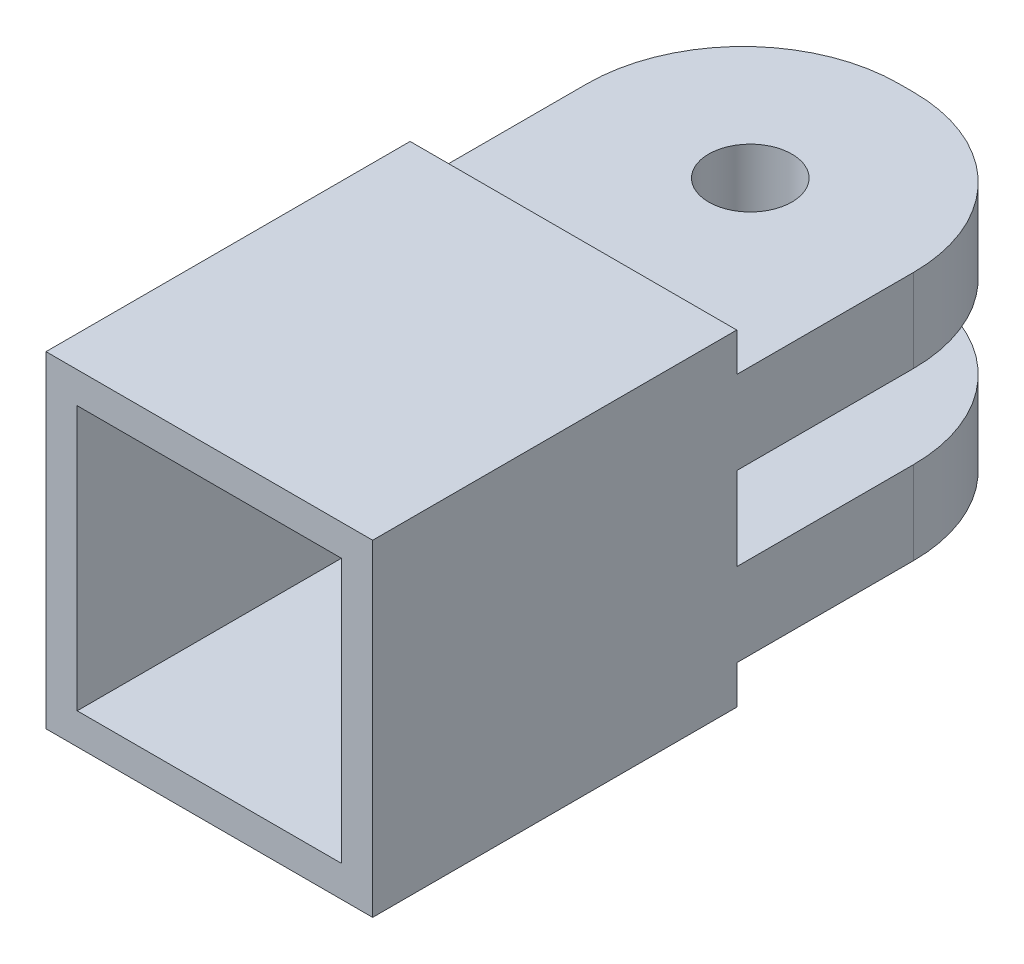
SolidWorks part; units mm, degrees
ref_plane "Front Plane" through (0, 0, 0) normal (0, 0, 1) x (1, 0, 0)
ref_plane "Top Plane" through (0, 0, 0) normal (0, 1, 0) x (1, 0, 0)
ref_plane "Right Plane" through (0, 0, 0) normal (1, 0, 0) x (0, 0, -1)
sketch "Sketch1" plane through (0, 0, 0) normal (0, 0, 1) x (1, 0, 0)
  line L0 (0, 34.2563) -> (0, -38.0151) construction
  line L1 (-50.9145, 0) -> (58.9447, 0) construction
  line L2 (-12.7, 12.7) -> (-12.7, -12.7)
  line L3 (-15.7, 15.7) -> (15.7, 15.7)
  line L4 (-15.7, 15.7) -> (-15.7, -15.7)
  line L5 (-15.7, -15.7) -> (15.7, -15.7)
  line L6 (15.7, 15.7) -> (15.7, -15.7)
  line L7 (-12.7, -12.7) -> (12.7, -12.7)
  line L8 (12.7, 12.7) -> (12.7, -12.7)
  line L9 (-12.7, 12.7) -> (12.7, 12.7)
  dimension "D1" = 15.7
  dimension "D2" = 15.7
  dimension "D3" = 15.7
  dimension "D4" = 15.7
  dimension "D5" = 3
extrude "Boss-Extrude1" add sketch "Sketch1" along normal blind 30
sketch "Sketch2" plane through (0, 0, 0) normal (0, 0, -1) x (-1, 0, 0)
  line L0 (15.7, 15.7) -> (15.7, -15.7)
  line L1 (15.7, -15.7) -> (-15.7, -15.7)
  line L2 (-15.7, -15.7) -> (-15.7, 15.7)
  line L3 (-15.7, 15.7) -> (15.7, 15.7)
extrude "Boss-Extrude2" add sketch "Sketch2" along normal blind 5
sketch "Sketch3" plane through (0, 0, -5) normal (0, 0, -1) x (-1, 0, 0)
  line L6 (-15.7, 12) -> (15.7, 12)
  line L7 (-15.7, 15.7) -> (-15.7, -15.7) construction
  line L8 (15.7, -15.7) -> (15.7, 15.7) construction
  line L9 (15.7, 12) -> (15.7, 4)
  line L10 (15.7, 4) -> (-15.7, 4)
  line L11 (-15.7, 4) -> (-15.7, 12)
  dimension "D1" = 8
  dimension "D2" = 4
extrude "Boss-Extrude3" add sketch "Sketch3" along normal blind 5
sketch "Sketch6" plane through (0, 12, 0) normal (0, 1, 0) x (1, 0, 0)
  line L0 (-15.7, 10) -> (-15.7, 22)
  line L1 (0.7, 37) -> (-0.7, 37)
  line L2 (15.7, 22) -> (15.7, 10)
  line L3 (15.7, 10) -> (-15.7, 10)
  arc A0 (-15.7, 22) -> (-0.7, 37) centre (-0.7, 22) cw
  arc A1 (0.7, 37) -> (15.7, 22) centre (0.7, 22) cw
  circle A2 centre (0, 22) radius 4
  point P10 (15.7, 37)
  dimension "D2" = 15
  dimension "D3" = 15
  dimension "D1" = 27
extrude "Boss-Extrude6" add sketch "Sketch6" against normal blind 8
mirror "Mirror1" about plane through (0, 0, 0) normal (0, 1, 0) of "Boss-Extrude6", "Boss-Extrude3"
